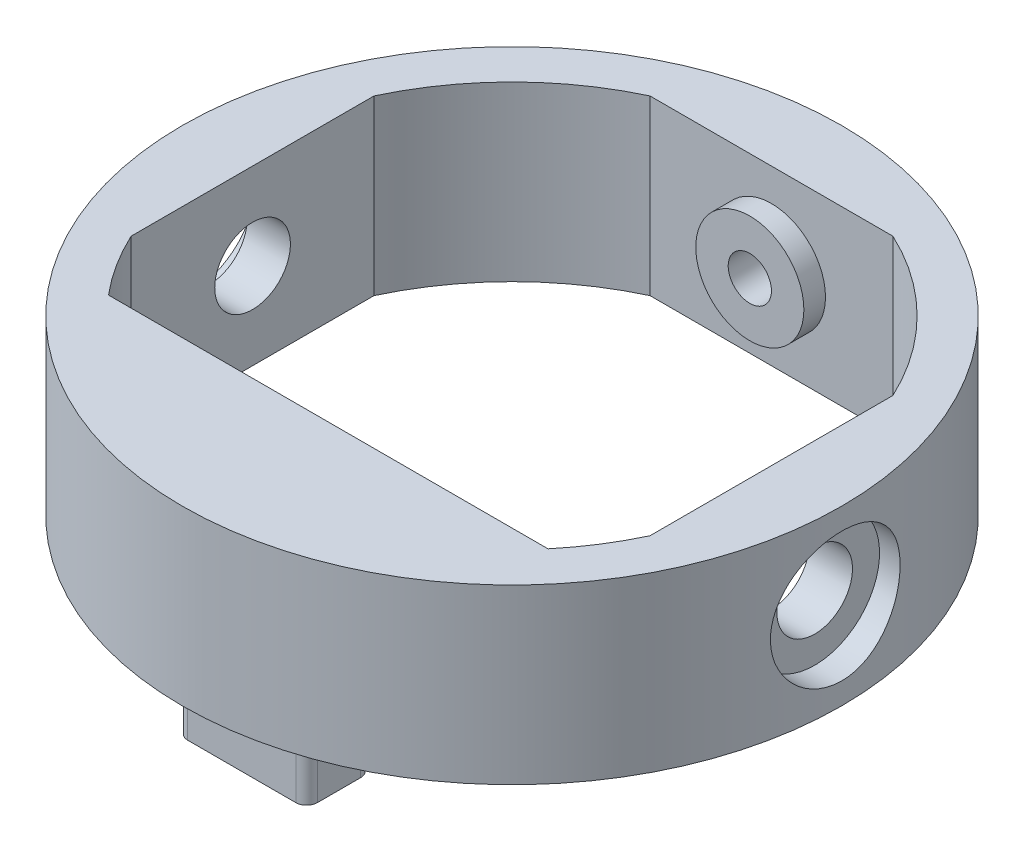
SolidWorks part; units mm, degrees
ref_plane "前视基准面" through (0, 0, 0) normal (0, 0, 1) x (1, 0, 0)
ref_plane "上视基准面" through (0, 0, 0) normal (0, 1, 0) x (1, 0, 0)
ref_plane "右视基准面" through (0, 0, 0) normal (1, 0, 0) x (0, 0, -1)
other "Configuration Table"
sketch "草图1" plane through (0, 0, 0) normal (0, 1, 0) x (1, 0, 0)
  circle A0 centre (0, 0) radius 15.25
  dimension "D1" = 30.5
extrude "凸台-拉伸1" add sketch "草图1" along normal mid plane 8
sketch "草图2" plane through (0, 4, 0) normal (0, 1, 0) x (1, 0, 0)
  line L0 (-12, 5.6181) -> (-12, -5.6181)
  line L5 (-10.1643, -8.5) -> (10.1643, -8.5)
  line L6 (12, -5.6181) -> (12, 5.6181)
  line L7 (0, 0) -> (0, 10.1515) construction
  arc A0 (12, 5.6181) -> (-12, 5.6181) centre (0, 0) ccw
  arc A2 (10.1643, -8.5) -> (12, -5.6181) centre (0, 0) ccw
  arc A4 (-12, -5.6181) -> (-10.1643, -8.5) centre (0, 0) ccw
  dimension "D1" = 13.25
  dimension "D2" = 24
  dimension "D4" = 8.5
extrude "切除-拉伸1" cut sketch "草图2" against normal through all
sketch "草图3" plane through (0, 0, 0) normal (0, 1, 0) x (1, 0, 0)
  line L0 (0, 0) -> (19.4793, 0) construction
  line L1 (12, 0) -> (12, 1.75)
  line L3 (12, 1.75) -> (14, 1.75)
  line L4 (14, 1.75) -> (14, 3)
  line L5 (14, 3) -> (20, 3)
  line L6 (20, 3) -> (20, 0)
  line L7 (12, 0) -> (20, 0)
  line L8 (12, -5.6181) -> (12, 5.6181) construction
  dimension "D1" = 3.5
  dimension "D2" = 6
  dimension "D3" = 14
  dimension "D4" = 20
revolve "切除-旋转4" cut sketch "草图3" angle 360 about L0
mirror "镜向1" about plane through (0, 0, 0) normal (1, 0, 0) of "切除-旋转4"
ref_plane "基准面1" through (0, 0, -12) normal (0, 0, 1) x (1, 0, 0)
sketch "草图17" plane through (0, 0, -12) normal (0, 0, 1) x (1, 0, 0)
  line L0 (5.6181, -4) -> (5.6181, 4)
  line L1 (-5.6181, 4) -> (-5.6181, -4)
  line L2 (-5.6181, 4) -> (-5.6181, -4)
  line L3 (5.6181, -4) -> (5.6181, 4)
  line L4 (-5.6181, 4) -> (5.6181, 4)
  line L5 (-5.6181, -4) -> (5.6181, -4)
extrude "凸台-拉伸3" add sketch "草图17" against normal up to surface up to face at (0, 0, -9.434)
sketch "草图16" plane through (0, 0, 0) normal (0, 0, 1) x (1, 0, 0)
  circle A2 centre (0, 0) radius 1
  dimension "D1" = 2
extrude "切除-拉伸7" cut sketch "草图16" against normal through all
sketch "草图18" plane through (0, 0, -12) normal (0, 0, 1) x (1, 0, 0)
  circle A0 centre (0, 0) radius 2.5
  circle A1 centre (0, 0) radius 1 construction
  circle A2 centre (0, 0) radius 1
  dimension "D1" = 5
extrude "凸台-拉伸4" add sketch "草图18" along normal blind 1
sketch "草图19" plane through (0, -4, 0) normal (0, -1, 0) x (1, 0, 0)
  line L0 (-10.1643, 8.5) -> (10.1643, 8.5) construction
  line L1 (-3, 12.5) -> (3, 12.5)
  line L2 (-3, 12.5) -> (-3, 9.5)
  line L3 (-3, 9.5) -> (3, 9.5)
  line L4 (3, 12.5) -> (3, 9.5)
  line L5 (-3, 12.5) -> (3, 9.5) construction
  line L6 (-3, 9.5) -> (3, 12.5) construction
  point P0 (0, 11)
  dimension "D1" = 1
  dimension "D2" = 6
  dimension "D3" = 3
extrude "凸台-拉伸5" add sketch "草图19" along normal blind 4
fillet "圆角1" radius 0.5 4 edges at (3, -6, 9.5) (3, -6, 12.5) (-3, -6, 9.5) (-3, -6, 12.5)
